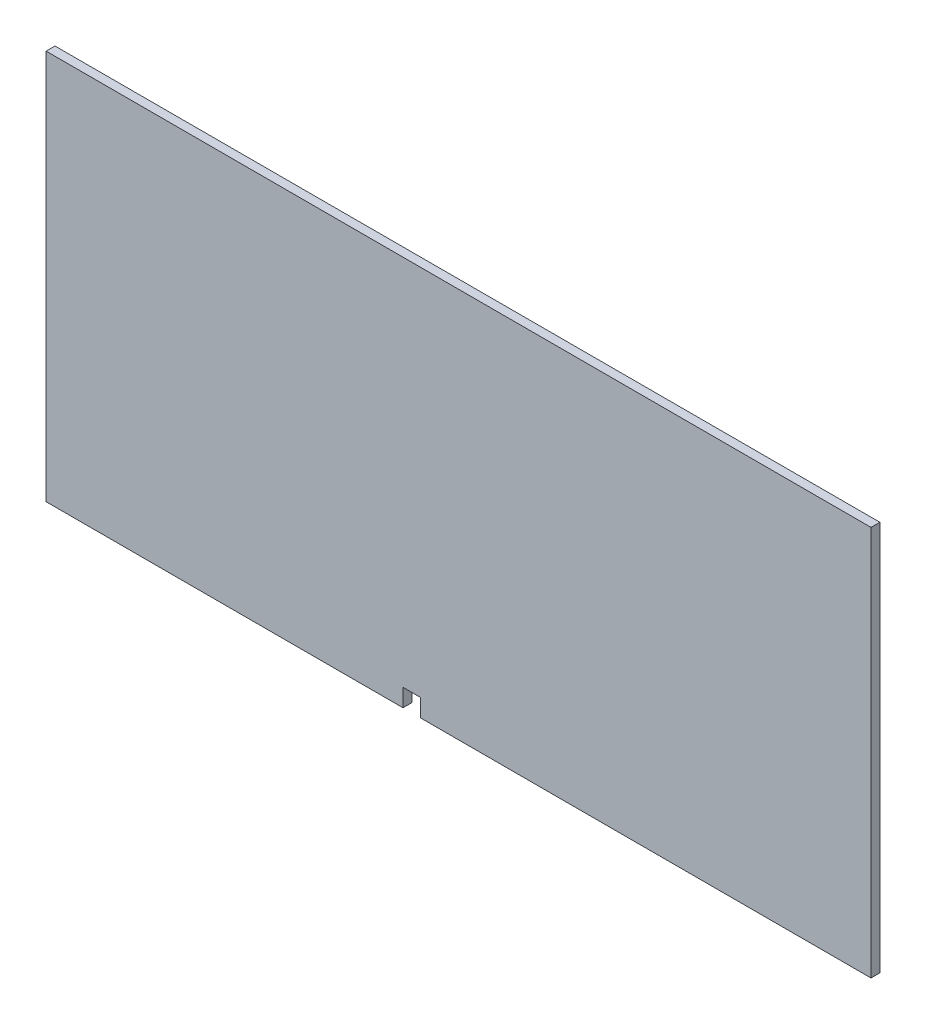
SolidWorks part; units mm, degrees
ref_plane "Front Plane" through (0, 0, 0) normal (0, 0, 1) x (1, 0, 0)
ref_plane "Top Plane" through (0, 0, 0) normal (0, 1, 0) x (1, 0, 0)
ref_plane "Right Plane" through (0, 0, 0) normal (1, 0, 0) x (0, 0, -1)
sketch "Sketch1" plane through (0, 0, 0) normal (0, 0, 1) x (1, 0, 0)
  line L1 (-232.5, -110) -> (232.5, -110)
  line L2 (-232.5, -110) -> (-232.5, 110)
  line L3 (-232.5, 110) -> (232.5, 110)
  line L4 (232.5, -110) -> (232.5, 110)
  line L5 (0, 110) -> (0, -110) construction
  line L6 (-232.5, 0) -> (232.5, 0) construction
  point P0 (0, 0)
  dimension "D1" = 465
  dimension "D2" = 220
extrude "Boss-Extrude1" add sketch "Sketch1" along normal blind 5
sketch "Sketch2" plane through (0, 0, 5) normal (0, 0, 1) x (1, 0, 0)
  line L0 (-232.5, -110) -> (232.5, -110) construction
  line L1 (-31.327, -110) -> (-21.327, -110)
  line L2 (-31.327, -110) -> (-31.327, -100)
  line L3 (-31.327, -100) -> (-21.327, -100)
  line L4 (-21.327, -110) -> (-21.327, -100)
  dimension "D1" = 10
  dimension "D2" = 10
extrude "Cut-Extrude1" cut sketch "Sketch2" against normal blind 10
